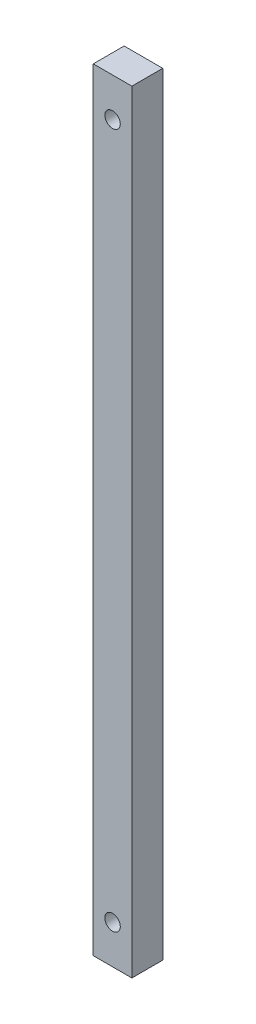
SolidWorks part; units mm, degrees
material "Thornel Mat VMA"
ref_plane "前视基准面" through (0, 0, 0) normal (0, 0, 1) x (1, 0, 0)
ref_plane "上视基准面" through (0, 0, 0) normal (0, 1, 0) x (1, 0, 0)
ref_plane "右视基准面" through (0, 0, 0) normal (1, 0, 0) x (0, 0, -1)
sketch "草图1" plane through (0, 0, 0) normal (0, 1, 0) x (1, 0, 0)
  line L1 (-2.5, 2) -> (2.5, 2)
  line L2 (-2.5, 2) -> (-2.5, -2)
  line L3 (-2.5, -2) -> (2.5, -2)
  line L4 (2.5, 2) -> (2.5, -2)
  line L5 (-2.5, 2) -> (2.5, -2) construction
  line L6 (-2.5, -2) -> (2.5, 2) construction
  point P0 (0, 0)
extrude "凸台-拉伸1" add sketch "草图1" along normal blind 100 contours L3 L4 L1 L2
sketch "草图2" plane through (0, 0, -2) normal (0, 0, -1) x (-1, 0, 0)
  line L0 (0, 0) -> (0, 100)
  line L1 (2.5, 100) -> (-2.5, 100) construction
  circle A0 centre (0, 5) radius 1
  circle A1 centre (0, 95) radius 1
  dimension "D1" = 5
  dimension "D2" = 5
extrude "切除-拉伸1" cut sketch "草图2" against normal blind 10 contours A0 | A1
